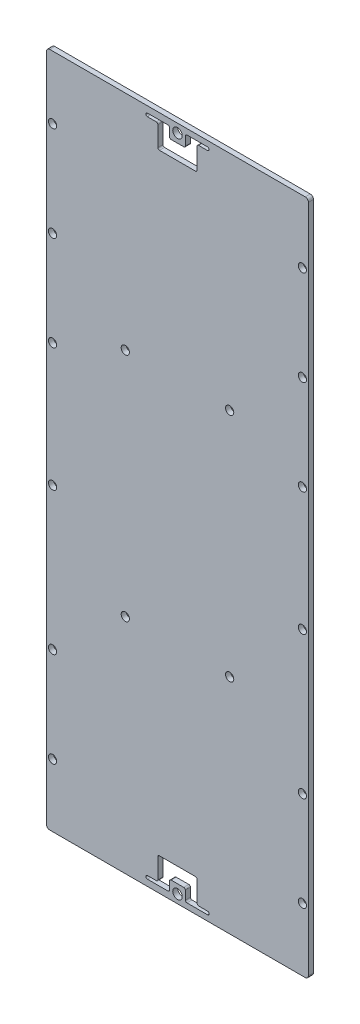
SolidWorks part; units mm, degrees
ref_plane "Front Plane" through (0, 0, 0) normal (0, 0, 1) x (1, 0, 0)
ref_plane "Top Plane" through (0, 0, 0) normal (0, 1, 0) x (1, 0, 0)
ref_plane "Right Plane" through (0, 0, 0) normal (1, 0, 0) x (0, 0, -1)
sketch "Sketch1" plane through (0, 0, 0) normal (0, 0, 1) x (1, 0, 0)
  line L0 (-37, -97) -> (37, -97) construction
  line L5 (-37, -95.4) -> (37, -95.4) construction
  line L6 (-37, -87) -> (37, -87) construction
  line L7 (-37, -85.4) -> (37, -85.4) construction
  line L8 (-37, -77) -> (37, -77) construction
  line L9 (-37, -75.4) -> (37, -75.4) construction
  line L10 (-37, -67) -> (37, -67) construction
  line L11 (-37, -65.4) -> (37, -65.4) construction
  line L12 (-37, -57) -> (37, -57) construction
  line L13 (-37, -55.4) -> (37, -55.4) construction
  line L14 (-37, -47) -> (37, -47) construction
  line L15 (-37, -45.4) -> (37, -45.4) construction
  line L16 (-37, -37) -> (37, -37) construction
  line L17 (-37, -35.4) -> (37, -35.4) construction
  line L18 (-37, -27) -> (37, -27) construction
  line L19 (-37, -25.4) -> (37, -25.4) construction
  line L20 (-37, -17) -> (37, -17) construction
  line L21 (-37, -15.4) -> (37, -15.4) construction
  line L22 (-37, 15.4) -> (37, 15.4) construction
  line L23 (-37, 17) -> (37, 17) construction
  line L24 (-37, 25.4) -> (37, 25.4) construction
  line L25 (-37, 27) -> (37, 27) construction
  line L26 (-37, 35.4) -> (37, 35.4) construction
  line L27 (-37, 37) -> (37, 37) construction
  line L28 (41.5, 107) -> (-41.5, 107)
  line L29 (-41.5, 107) -> (-41.5, 99)
  line L30 (-41.5, 99) -> (-41.5, 93.95)
  line L31 (-41.5, 93.95) -> (-41.5, 88.45)
  line L32 (-41.5, 88.45) -> (-41.5, 33.95)
  line L33 (-41.5, 33.95) -> (-41.5, 28.45)
  line L34 (-41.5, 28.45) -> (-41.5, -28.45)
  line L35 (-41.5, -28.45) -> (-41.5, -33.95)
  line L36 (-41.5, -33.95) -> (-41.5, -88.45)
  line L37 (-41.5, -88.45) -> (-41.5, -93.95)
  line L38 (-41.5, -93.95) -> (-41.5, -99)
  line L39 (-41.5, -99) -> (-41.5, -107)
  line L40 (-41.5, -107) -> (41.5, -107)
  line L41 (41.5, -107) -> (41.5, -99)
  line L42 (41.5, -99) -> (41.5, -93.95)
  line L43 (41.5, -93.95) -> (41.5, -88.45)
  line L44 (41.5, -88.45) -> (41.5, -33.95)
  line L45 (41.5, -33.95) -> (41.5, -28.45)
  line L46 (41.5, -28.45) -> (41.5, 28.45)
  line L47 (41.5, 28.45) -> (41.5, 33.95)
  line L48 (41.5, 33.95) -> (41.5, 88.45)
  line L49 (41.5, 88.45) -> (41.5, 93.95)
  line L50 (41.5, 93.95) -> (41.5, 99)
  line L51 (41.5, 99) -> (41.5, 107)
  line L52 (41.5, 107) -> (-41.5, 107)
  line L53 (-41.5, 107) -> (-41.5, 99)
  line L54 (-41.5, 99) -> (-41.5, 93.95)
  line L55 (-41.5, 93.95) -> (-41.5, 88.45)
  line L56 (-41.5, 88.45) -> (-41.5, 33.95)
  line L57 (-41.5, 33.95) -> (-41.5, 28.45)
  line L58 (-41.5, 28.45) -> (-41.5, -28.45)
  line L59 (-41.5, -28.45) -> (-41.5, -33.95)
  line L60 (-41.5, -33.95) -> (-41.5, -88.45)
  line L61 (-41.5, -88.45) -> (-41.5, -93.95)
  line L62 (-41.5, -93.95) -> (-41.5, -99)
  line L63 (-41.5, -99) -> (-41.5, -107)
  line L64 (-41.5, -107) -> (41.5, -107)
  line L65 (41.5, -107) -> (41.5, -99)
  line L66 (41.5, -99) -> (41.5, -93.95)
  line L67 (41.5, -93.95) -> (41.5, -88.45)
  line L68 (41.5, -88.45) -> (41.5, -33.95)
  line L69 (41.5, -33.95) -> (41.5, -28.45)
  line L70 (41.5, -28.45) -> (41.5, 28.45)
  line L71 (41.5, 28.45) -> (41.5, 33.95)
  line L72 (41.5, 33.95) -> (41.5, 88.45)
  line L73 (41.5, 88.45) -> (41.5, 93.95)
  line L74 (41.5, 93.95) -> (41.5, 99)
  line L75 (41.5, 99) -> (41.5, 107)
  line L76 (-37, 45.4) -> (37, 45.4) construction
  line L77 (-37, 47) -> (37, 47) construction
  line L78 (-37, 55.4) -> (37, 55.4) construction
  line L79 (-37, 57) -> (37, 57) construction
  line L80 (-37, 65.4) -> (37, 65.4) construction
  line L81 (-37, 67) -> (37, 67) construction
  line L82 (-37, 75.4) -> (37, 75.4) construction
  line L83 (-37, 77) -> (37, 77) construction
  line L84 (-37, 85.4) -> (37, 85.4) construction
  line L85 (-37, 87) -> (37, 87) construction
  line L86 (-37, 95.4) -> (37, 95.4) construction
  line L87 (-37, 97) -> (37, 97) construction
  line L88 (-37, -97) -> (37, -97) construction
  line L89 (-37, -95.4) -> (37, -95.4) construction
  line L90 (-37, -87) -> (37, -87) construction
  line L91 (-37, -85.4) -> (37, -85.4) construction
  line L92 (-37, -77) -> (37, -77) construction
  line L93 (-37, -75.4) -> (37, -75.4) construction
  line L94 (-37, -67) -> (37, -67) construction
  line L95 (-37, -65.4) -> (37, -65.4) construction
  line L96 (-37, -57) -> (37, -57) construction
  line L97 (-37, -55.4) -> (37, -55.4) construction
  line L98 (-37, -47) -> (37, -47) construction
  line L99 (-37, -45.4) -> (37, -45.4) construction
  line L100 (-37, -37) -> (37, -37) construction
  line L101 (-37, -35.4) -> (37, -35.4) construction
  line L102 (-37, -27) -> (37, -27) construction
  line L103 (-37, -25.4) -> (37, -25.4) construction
  line L104 (-37, -17) -> (37, -17) construction
  line L105 (-37, -15.4) -> (37, -15.4) construction
  line L106 (-37, 15.4) -> (37, 15.4) construction
  line L107 (-37, 17) -> (37, 17) construction
  line L108 (-37, 25.4) -> (37, 25.4) construction
  line L109 (-37, 27) -> (37, 27) construction
  line L110 (-37, 35.4) -> (37, 35.4) construction
  line L111 (-37, 37) -> (37, 37) construction
  line L112 (-37, 45.4) -> (37, 45.4) construction
  line L113 (-37, 47) -> (37, 47) construction
  line L114 (-37, 55.4) -> (37, 55.4) construction
  line L115 (-37, 57) -> (37, 57) construction
  line L116 (-37, 65.4) -> (37, 65.4) construction
  line L117 (-37, 67) -> (37, 67) construction
  line L118 (-37, 75.4) -> (37, 75.4) construction
  line L119 (-37, 77) -> (37, 77) construction
  line L120 (-37, 85.4) -> (37, 85.4) construction
  line L121 (-37, 87) -> (37, 87) construction
  line L122 (-37, 95.4) -> (37, 95.4) construction
  line L123 (-37, 97) -> (37, 97) construction
  line L124 (41.4, 106.9) -> (-41.4, 106.9)
  line L125 (-41.4, 106.9) -> (-41.4, 99)
  line L126 (-41.4, 99) -> (-41.4, 93.95)
  line L127 (-41.4, 93.95) -> (-41.4, 88.45)
  line L128 (-41.4, 88.45) -> (-41.4, 33.95)
  line L129 (-41.4, 33.95) -> (-41.4, 28.45)
  line L130 (-41.4, 28.45) -> (-41.4, -28.45)
  line L131 (-41.4, -28.45) -> (-41.4, -33.95)
  line L132 (-41.4, -33.95) -> (-41.4, -88.45)
  line L133 (-41.4, -88.45) -> (-41.4, -93.95)
  line L134 (-41.4, -93.95) -> (-41.4, -99)
  line L135 (-41.4, -99) -> (-41.4, -106.9)
  line L136 (-41.4, -106.9) -> (41.4, -106.9)
  line L137 (41.4, -106.9) -> (41.4, -99)
  line L138 (41.4, -99) -> (41.4, -93.95)
  line L139 (41.4, -93.95) -> (41.4, -88.45)
  line L140 (41.4, -88.45) -> (41.4, -33.95)
  line L141 (41.4, -33.95) -> (41.4, -28.45)
  line L142 (41.4, -28.45) -> (41.4, 28.45)
  line L143 (41.4, 28.45) -> (41.4, 33.95)
  line L144 (41.4, 33.95) -> (41.4, 88.45)
  line L145 (41.4, 88.45) -> (41.4, 93.95)
  line L146 (41.4, 93.95) -> (41.4, 99)
  line L147 (41.4, 99) -> (41.4, 106.9)
  circle A0 centre (-39.5, 87) radius 0.8 construction
  circle A2 centre (-39.5, 57) radius 0.8 construction
  circle A5 centre (-39.5, 27) radius 0.8 construction
  circle A6 centre (-16.5, 36.5) radius 0.8 construction
  circle A7 centre (-39.5, -12) radius 0.8 construction
  circle A9 centre (-16.5, -36.5) radius 0.8 construction
  circle A11 centre (-39.5, -57) radius 0.8 construction
  circle A13 centre (-39.5, -87) radius 0.8 construction
  circle A16 centre (0, -104.2) radius 0.8 construction
  circle A19 centre (39.5, -87) radius 0.8 construction
  circle A21 centre (39.5, -57) radius 0.8 construction
  circle A22 centre (16.5, -36.5) radius 0.8 construction
  circle A25 centre (39.5, -12) radius 0.8 construction
  circle A27 centre (39.5, 27) radius 0.8 construction
  circle A28 centre (16.5, 36.5) radius 0.8 construction
  circle A30 centre (39.5, 57) radius 0.8 construction
  circle A32 centre (39.5, 87) radius 0.8 construction
  circle A35 centre (0, 104.2) radius 0.8 construction
  circle A38 centre (-39.5, 87) radius 0.8
  circle A40 centre (-39.5, 57) radius 0.8
  circle A43 centre (-39.5, 27) radius 0.8
  circle A44 centre (-16.5, 36.5) radius 0.8
  circle A45 centre (-39.5, -12) radius 0.8
  circle A47 centre (-16.5, -36.5) radius 0.8
  circle A49 centre (-39.5, -57) radius 0.8
  circle A51 centre (-39.5, -87) radius 0.8
  circle A54 centre (0, -104.2) radius 0.8
  circle A57 centre (39.5, -87) radius 0.8
  circle A59 centre (39.5, -57) radius 0.8
  circle A60 centre (16.5, -36.5) radius 0.8
  circle A63 centre (39.5, -12) radius 0.8
  circle A65 centre (39.5, 27) radius 0.8
  circle A66 centre (16.5, 36.5) radius 0.8
  circle A68 centre (39.5, 57) radius 0.8
  circle A70 centre (39.5, 87) radius 0.8
  circle A73 centre (0, 104.2) radius 0.8
  dimension "D1" = 0
  dimension "D2" = 0.1
extrude "pcb extrude" add sketch "Sketch1" along normal blind 1.6
sketch "connector locations" plane through (0, 0, 1.6) normal (0, 0, 1) x (1, 0, 0)
  line L0 (-37, 97) -> (37, 97) construction
  line L1 (-33.4182, 100.556) -> (-8.7802, 100.556)
  line L2 (-33.4182, 100.556) -> (-33.4182, 99.159)
  line L3 (-33.4182, 99.159) -> (-8.7802, 99.159)
  line L4 (-8.7802, 100.556) -> (-8.7802, 99.159)
  line L5 (-33.4182, 100.556) -> (-8.7802, 99.159) construction
  line L6 (-33.4182, 99.159) -> (-8.7802, 100.556) construction
  line L7 (-37, 87) -> (37, 87) construction
  line L8 (-33.4182, 90.556) -> (-21.5818, 90.556)
  line L9 (-33.4182, 90.556) -> (-33.4182, 89.159)
  line L10 (-33.4182, 89.159) -> (-21.5818, 89.159)
  line L11 (-21.5818, 90.556) -> (-21.5818, 89.159)
  line L12 (-33.4182, 90.556) -> (-21.5818, 89.159) construction
  line L13 (-33.4182, 89.159) -> (-21.5818, 90.556) construction
  line L14 (0, -55) -> (0, 55) construction
  line L15 (-12.319, 90.556) -> (12.319, 90.556)
  line L16 (-12.319, 90.556) -> (-12.319, 89.159)
  line L17 (-12.319, 89.159) -> (12.319, 89.159)
  line L18 (12.319, 90.556) -> (12.319, 89.159)
  line L19 (-12.319, 90.556) -> (12.319, 89.159) construction
  line L20 (-12.319, 89.159) -> (12.319, 90.556) construction
  line L21 (-37, -85.4) -> (37, -85.4) construction
  line L22 (-33.4182, -91.844) -> (-8.7802, -91.844)
  line L23 (-33.4182, -91.844) -> (-33.4182, -93.241)
  line L24 (-33.4182, -93.241) -> (-8.7802, -93.241)
  line L25 (-8.7802, -91.844) -> (-8.7802, -93.241)
  line L26 (-33.4182, -91.844) -> (-8.7802, -93.241) construction
  line L27 (-33.4182, -93.241) -> (-8.7802, -91.844) construction
  line L28 (-33.4182, -81.844) -> (-21.5818, -81.844)
  line L29 (-33.4182, -81.844) -> (-33.4182, -83.241)
  line L30 (-33.4182, -83.241) -> (-21.5818, -83.241)
  line L31 (-21.5818, -81.844) -> (-21.5818, -83.241)
  line L32 (-33.4182, -81.844) -> (-21.5818, -83.241) construction
  line L33 (-33.4182, -83.241) -> (-21.5818, -81.844) construction
  line L34 (-12.319, -81.844) -> (12.319, -81.844)
  line L35 (-12.319, -81.844) -> (-12.319, -83.241)
  line L36 (-12.319, -83.241) -> (12.319, -83.241)
  line L37 (12.319, -81.844) -> (12.319, -83.241)
  line L38 (-12.319, -81.844) -> (12.319, -83.241) construction
  line L39 (-12.319, -83.241) -> (12.319, -81.844) construction
  line L40 (-37, -95.4) -> (37, -95.4) construction
  line L41 (-33.4182, 80.556) -> (-33.4182, 79.159)
  line L42 (-33.4182, 80.556) -> (-21.5818, 80.556)
  line L43 (-21.5818, 80.556) -> (-21.5818, 79.159)
  line L44 (-33.4182, 79.159) -> (-21.5818, 79.159)
  line L45 (-33.4182, 80.556) -> (-21.5818, 79.159) construction
  line L46 (-33.4182, 79.159) -> (-21.5818, 80.556) construction
  line L47 (-12.319, 80.556) -> (-12.319, 79.159)
  line L48 (-12.319, 80.556) -> (12.319, 80.556)
  line L49 (12.319, 80.556) -> (12.319, 79.159)
  line L50 (-12.319, 79.159) -> (12.319, 79.159)
  line L51 (-12.319, 80.556) -> (12.319, 79.159) construction
  line L52 (-12.319, 79.159) -> (12.319, 80.556) construction
  line L53 (-33.4182, 70.556) -> (-33.4182, 69.159)
  line L54 (-33.4182, 70.556) -> (-21.5818, 70.556)
  line L55 (-21.5818, 70.556) -> (-21.5818, 69.159)
  line L56 (-33.4182, 69.159) -> (-21.5818, 69.159)
  line L57 (-33.4182, 70.556) -> (-21.5818, 69.159) construction
  line L58 (-33.4182, 69.159) -> (-21.5818, 70.556) construction
  line L59 (-12.319, 70.556) -> (-12.319, 69.159)
  line L60 (-12.319, 70.556) -> (12.319, 70.556)
  line L61 (12.319, 70.556) -> (12.319, 69.159)
  line L62 (-12.319, 69.159) -> (12.319, 69.159)
  line L63 (-12.319, 70.556) -> (12.319, 69.159) construction
  line L64 (-12.319, 69.159) -> (12.319, 70.556) construction
  line L65 (-33.4182, 60.556) -> (-33.4182, 59.159)
  line L66 (-33.4182, 60.556) -> (-21.5818, 60.556)
  line L67 (-21.5818, 60.556) -> (-21.5818, 59.159)
  line L68 (-33.4182, 59.159) -> (-21.5818, 59.159)
  line L69 (-33.4182, 60.556) -> (-21.5818, 59.159) construction
  line L70 (-33.4182, 59.159) -> (-21.5818, 60.556) construction
  line L71 (-12.319, 60.556) -> (-12.319, 59.159)
  line L72 (-12.319, 60.556) -> (12.319, 60.556)
  line L73 (12.319, 60.556) -> (12.319, 59.159)
  line L74 (-12.319, 59.159) -> (12.319, 59.159)
  line L75 (-12.319, 60.556) -> (12.319, 59.159) construction
  line L76 (-12.319, 59.159) -> (12.319, 60.556) construction
  line L77 (-33.4182, 50.556) -> (-33.4182, 49.159)
  line L78 (-33.4182, 50.556) -> (-21.5818, 50.556)
  line L79 (-21.5818, 50.556) -> (-21.5818, 49.159)
  line L80 (-33.4182, 49.159) -> (-21.5818, 49.159)
  line L81 (-33.4182, 50.556) -> (-21.5818, 49.159) construction
  line L82 (-33.4182, 49.159) -> (-21.5818, 50.556) construction
  line L83 (-12.319, 50.556) -> (-12.319, 49.159)
  line L84 (-12.319, 50.556) -> (12.319, 50.556)
  line L85 (12.319, 50.556) -> (12.319, 49.159)
  line L86 (-12.319, 49.159) -> (12.319, 49.159)
  line L87 (-12.319, 50.556) -> (12.319, 49.159) construction
  line L88 (-12.319, 49.159) -> (12.319, 50.556) construction
  line L89 (-33.4182, 40.556) -> (-33.4182, 39.159)
  line L90 (-33.4182, 40.556) -> (-21.5818, 40.556)
  line L91 (-21.5818, 40.556) -> (-21.5818, 39.159)
  line L92 (-33.4182, 39.159) -> (-21.5818, 39.159)
  line L93 (-33.4182, 40.556) -> (-21.5818, 39.159) construction
  line L94 (-33.4182, 39.159) -> (-21.5818, 40.556) construction
  line L95 (-12.319, 40.556) -> (-12.319, 39.159)
  line L96 (-12.319, 40.556) -> (12.319, 40.556)
  line L97 (12.319, 40.556) -> (12.319, 39.159)
  line L98 (-12.319, 39.159) -> (12.319, 39.159)
  line L99 (-12.319, 40.556) -> (12.319, 39.159) construction
  line L100 (-12.319, 39.159) -> (12.319, 40.556) construction
  line L101 (-33.4182, 30.556) -> (-33.4182, 29.159)
  line L102 (-33.4182, 30.556) -> (-21.5818, 30.556)
  line L103 (-21.5818, 30.556) -> (-21.5818, 29.159)
  line L104 (-33.4182, 29.159) -> (-21.5818, 29.159)
  line L105 (-33.4182, 30.556) -> (-21.5818, 29.159) construction
  line L106 (-33.4182, 29.159) -> (-21.5818, 30.556) construction
  line L107 (-12.319, 30.556) -> (-12.319, 29.159)
  line L108 (-12.319, 30.556) -> (12.319, 30.556)
  line L109 (12.319, 30.556) -> (12.319, 29.159)
  line L110 (-12.319, 29.159) -> (12.319, 29.159)
  line L111 (-12.319, 30.556) -> (12.319, 29.159) construction
  line L112 (-12.319, 29.159) -> (12.319, 30.556) construction
  line L113 (-33.4182, 20.556) -> (-33.4182, 19.159)
  line L114 (-33.4182, 20.556) -> (-21.5818, 20.556)
  line L115 (-21.5818, 20.556) -> (-21.5818, 19.159)
  line L116 (-33.4182, 19.159) -> (-21.5818, 19.159)
  line L117 (-33.4182, 20.556) -> (-21.5818, 19.159) construction
  line L118 (-33.4182, 19.159) -> (-21.5818, 20.556) construction
  line L119 (-12.319, 20.556) -> (-12.319, 19.159)
  line L120 (-12.319, 20.556) -> (12.319, 20.556)
  line L121 (12.319, 20.556) -> (12.319, 19.159)
  line L122 (-12.319, 19.159) -> (12.319, 19.159)
  line L123 (-12.319, 20.556) -> (12.319, 19.159) construction
  line L124 (-12.319, 19.159) -> (12.319, 20.556) construction
  line L125 (-33.4182, 10.556) -> (-33.4182, 9.159)
  line L126 (-33.4182, 10.556) -> (-21.5818, 10.556)
  line L127 (-21.5818, 10.556) -> (-21.5818, 9.159)
  line L128 (-33.4182, 9.159) -> (-21.5818, 9.159)
  line L129 (-33.4182, 10.556) -> (-21.5818, 9.159) construction
  line L130 (-33.4182, 9.159) -> (-21.5818, 10.556) construction
  line L131 (-12.319, 10.556) -> (-12.319, 9.159)
  line L132 (-12.319, 10.556) -> (12.319, 10.556)
  line L133 (12.319, 10.556) -> (12.319, 9.159)
  line L134 (-12.319, 9.159) -> (12.319, 9.159)
  line L135 (-12.319, 10.556) -> (12.319, 9.159) construction
  line L136 (-12.319, 9.159) -> (12.319, 10.556) construction
  line L137 (0, 89.8575) -> (0, 79.8575) construction
  line L138 (-33.4182, -71.844) -> (-33.4182, -73.241)
  line L139 (-33.4182, -71.844) -> (-21.5818, -71.844)
  line L140 (-21.5818, -71.844) -> (-21.5818, -73.241)
  line L141 (-33.4182, -73.241) -> (-21.5818, -73.241)
  line L142 (-33.4182, -73.241) -> (-21.5818, -71.844) construction
  line L143 (-33.4182, -71.844) -> (-21.5818, -73.241) construction
  line L144 (-12.319, -71.844) -> (-12.319, -73.241)
  line L145 (-12.319, -71.844) -> (12.319, -71.844)
  line L146 (12.319, -71.844) -> (12.319, -73.241)
  line L147 (-12.319, -73.241) -> (12.319, -73.241)
  line L148 (-12.319, -73.241) -> (12.319, -71.844) construction
  line L149 (-12.319, -71.844) -> (12.319, -73.241) construction
  line L150 (-33.4182, -61.844) -> (-33.4182, -63.241)
  line L151 (-33.4182, -61.844) -> (-21.5818, -61.844)
  line L152 (-21.5818, -61.844) -> (-21.5818, -63.241)
  line L153 (-33.4182, -63.241) -> (-21.5818, -63.241)
  line L154 (-33.4182, -63.241) -> (-21.5818, -61.844) construction
  line L155 (-33.4182, -61.844) -> (-21.5818, -63.241) construction
  line L156 (-12.319, -61.844) -> (-12.319, -63.241)
  line L157 (-12.319, -61.844) -> (12.319, -61.844)
  line L158 (12.319, -61.844) -> (12.319, -63.241)
  line L159 (-12.319, -63.241) -> (12.319, -63.241)
  line L160 (-12.319, -63.241) -> (12.319, -61.844) construction
  line L161 (-12.319, -61.844) -> (12.319, -63.241) construction
  line L162 (-33.4182, -51.844) -> (-33.4182, -53.241)
  line L163 (-33.4182, -51.844) -> (-21.5818, -51.844)
  line L164 (-21.5818, -51.844) -> (-21.5818, -53.241)
  line L165 (-33.4182, -53.241) -> (-21.5818, -53.241)
  line L166 (-33.4182, -53.241) -> (-21.5818, -51.844) construction
  line L167 (-33.4182, -51.844) -> (-21.5818, -53.241) construction
  line L168 (-12.319, -51.844) -> (-12.319, -53.241)
  line L169 (-12.319, -51.844) -> (12.319, -51.844)
  line L170 (12.319, -51.844) -> (12.319, -53.241)
  line L171 (-12.319, -53.241) -> (12.319, -53.241)
  line L172 (-12.319, -53.241) -> (12.319, -51.844) construction
  line L173 (-12.319, -51.844) -> (12.319, -53.241) construction
  line L174 (-33.4182, -41.844) -> (-33.4182, -43.241)
  line L175 (-33.4182, -41.844) -> (-21.5818, -41.844)
  line L176 (-21.5818, -41.844) -> (-21.5818, -43.241)
  line L177 (-33.4182, -43.241) -> (-21.5818, -43.241)
  line L178 (-33.4182, -43.241) -> (-21.5818, -41.844) construction
  line L179 (-33.4182, -41.844) -> (-21.5818, -43.241) construction
  line L180 (-12.319, -41.844) -> (-12.319, -43.241)
  line L181 (-12.319, -41.844) -> (12.319, -41.844)
  line L182 (12.319, -41.844) -> (12.319, -43.241)
  line L183 (-12.319, -43.241) -> (12.319, -43.241)
  line L184 (-12.319, -43.241) -> (12.319, -41.844) construction
  line L185 (-12.319, -41.844) -> (12.319, -43.241) construction
  line L186 (-33.4182, -31.844) -> (-33.4182, -33.241)
  line L187 (-33.4182, -31.844) -> (-21.5818, -31.844)
  line L188 (-21.5818, -31.844) -> (-21.5818, -33.241)
  line L189 (-33.4182, -33.241) -> (-21.5818, -33.241)
  line L190 (-33.4182, -33.241) -> (-21.5818, -31.844) construction
  line L191 (-33.4182, -31.844) -> (-21.5818, -33.241) construction
  line L192 (-12.319, -31.844) -> (-12.319, -33.241)
  line L193 (-12.319, -31.844) -> (12.319, -31.844)
  line L194 (12.319, -31.844) -> (12.319, -33.241)
  line L195 (-12.319, -33.241) -> (12.319, -33.241)
  line L196 (-12.319, -33.241) -> (12.319, -31.844) construction
  line L197 (-12.319, -31.844) -> (12.319, -33.241) construction
  line L198 (-33.4182, -21.844) -> (-33.4182, -23.241)
  line L199 (-33.4182, -21.844) -> (-21.5818, -21.844)
  line L200 (-21.5818, -21.844) -> (-21.5818, -23.241)
  line L201 (-33.4182, -23.241) -> (-21.5818, -23.241)
  line L202 (-33.4182, -23.241) -> (-21.5818, -21.844) construction
  line L203 (-33.4182, -21.844) -> (-21.5818, -23.241) construction
  line L204 (-12.319, -21.844) -> (-12.319, -23.241)
  line L205 (-12.319, -21.844) -> (12.319, -21.844)
  line L206 (12.319, -21.844) -> (12.319, -23.241)
  line L207 (-12.319, -23.241) -> (12.319, -23.241)
  line L208 (-12.319, -23.241) -> (12.319, -21.844) construction
  line L209 (-12.319, -21.844) -> (12.319, -23.241) construction
  line L210 (-33.4182, -11.844) -> (-33.4182, -13.241)
  line L211 (-33.4182, -11.844) -> (-21.5818, -11.844)
  line L212 (-21.5818, -11.844) -> (-21.5818, -13.241)
  line L213 (-33.4182, -13.241) -> (-21.5818, -13.241)
  line L214 (-33.4182, -13.241) -> (-21.5818, -11.844) construction
  line L215 (-33.4182, -11.844) -> (-21.5818, -13.241) construction
  line L216 (-12.319, -11.844) -> (-12.319, -13.241)
  line L217 (-12.319, -11.844) -> (12.319, -11.844)
  line L218 (12.319, -11.844) -> (12.319, -13.241)
  line L219 (-12.319, -13.241) -> (12.319, -13.241)
  line L220 (-12.319, -13.241) -> (12.319, -11.844) construction
  line L221 (-12.319, -11.844) -> (12.319, -13.241) construction
  line L222 (-33.4182, -1.844) -> (-33.4182, -3.241)
  line L223 (-33.4182, -1.844) -> (-21.5818, -1.844)
  line L224 (-21.5818, -1.844) -> (-21.5818, -3.241)
  line L225 (-33.4182, -3.241) -> (-21.5818, -3.241)
  line L226 (-33.4182, -3.241) -> (-21.5818, -1.844) construction
  line L227 (-33.4182, -1.844) -> (-21.5818, -3.241) construction
  line L228 (-12.319, -1.844) -> (-12.319, -3.241)
  line L229 (-12.319, -1.844) -> (12.319, -1.844)
  line L230 (12.319, -1.844) -> (12.319, -3.241)
  line L231 (-12.319, -3.241) -> (12.319, -3.241)
  line L232 (-12.319, -3.241) -> (12.319, -1.844) construction
  line L233 (-12.319, -1.844) -> (12.319, -3.241) construction
  line L234 (0, -82.5425) -> (0, -72.5425) construction
  line L235 (27.42, 96.09) -> (29.58, 98.27) construction
  line L236 (27.42, 98.27) -> (29.58, 96.09) construction
  line L237 (33.42, 98.27) -> (35.58, 96.09) construction
  line L238 (33.42, 96.09) -> (35.58, 98.27) construction
  line L239 (21.42, 96.09) -> (23.58, 98.27) construction
  line L240 (21.42, 98.27) -> (23.58, 96.09) construction
  line L241 (27.42, 86.09) -> (29.58, 88.27) construction
  line L242 (27.42, 88.27) -> (29.58, 86.09) construction
  line L243 (21.42, 86.09) -> (23.58, 88.27) construction
  line L244 (21.42, 88.27) -> (23.58, 86.09) construction
  line L245 (27.42, 76.09) -> (29.58, 78.27) construction
  line L246 (27.42, 78.27) -> (29.58, 76.09) construction
  line L247 (21.42, 76.09) -> (23.58, 78.27) construction
  line L248 (21.42, 78.27) -> (23.58, 76.09) construction
  line L249 (27.42, 66.09) -> (29.58, 68.27) construction
  line L250 (27.42, 68.27) -> (29.58, 66.09) construction
  line L251 (21.42, 66.09) -> (23.58, 68.27) construction
  line L252 (21.42, 68.27) -> (23.58, 66.09) construction
  line L253 (27.42, 56.09) -> (29.58, 58.27) construction
  line L254 (27.42, 58.27) -> (29.58, 56.09) construction
  line L255 (21.42, 56.09) -> (23.58, 58.27) construction
  line L256 (21.42, 58.27) -> (23.58, 56.09) construction
  line L257 (27.42, 46.09) -> (29.58, 48.27) construction
  line L258 (27.42, 48.27) -> (29.58, 46.09) construction
  line L259 (21.42, 46.09) -> (23.58, 48.27) construction
  line L260 (21.42, 48.27) -> (23.58, 46.09) construction
  line L261 (27.42, 36.09) -> (29.58, 38.27) construction
  line L262 (27.42, 38.27) -> (29.58, 36.09) construction
  line L263 (21.42, 36.09) -> (23.58, 38.27) construction
  line L264 (21.42, 38.27) -> (23.58, 36.09) construction
  line L265 (27.42, 26.09) -> (29.58, 28.27) construction
  line L266 (27.42, 28.27) -> (29.58, 26.09) construction
  line L267 (21.42, 26.09) -> (23.58, 28.27) construction
  line L268 (21.42, 28.27) -> (23.58, 26.09) construction
  line L269 (27.42, 16.09) -> (29.58, 18.27) construction
  line L270 (27.42, 18.27) -> (29.58, 16.09) construction
  line L271 (21.42, 16.09) -> (23.58, 18.27) construction
  line L272 (21.42, 18.27) -> (23.58, 16.09) construction
  line L273 (27.42, 6.09) -> (29.58, 8.27) construction
  line L274 (27.42, 8.27) -> (29.58, 6.09) construction
  line L275 (21.42, 6.09) -> (23.58, 8.27) construction
  line L276 (21.42, 8.27) -> (23.58, 6.09) construction
  line L277 (33.42, 86.09) -> (35.58, 88.27) construction
  line L278 (33.42, 88.27) -> (35.58, 86.09) construction
  line L279 (33.42, 76.09) -> (35.58, 78.27) construction
  line L280 (33.42, 78.27) -> (35.58, 76.09) construction
  line L281 (33.42, 66.09) -> (35.58, 68.27) construction
  line L282 (33.42, 68.27) -> (35.58, 66.09) construction
  line L283 (33.42, 56.09) -> (35.58, 58.27) construction
  line L284 (33.42, 58.27) -> (35.58, 56.09) construction
  line L285 (33.42, 46.09) -> (35.58, 48.27) construction
  line L286 (33.42, 48.27) -> (35.58, 46.09) construction
  line L287 (33.42, 36.09) -> (35.58, 38.27) construction
  line L288 (33.42, 38.27) -> (35.58, 36.09) construction
  line L289 (33.42, 26.09) -> (35.58, 28.27) construction
  line L290 (33.42, 28.27) -> (35.58, 26.09) construction
  line L291 (33.42, 16.09) -> (35.58, 18.27) construction
  line L292 (33.42, 18.27) -> (35.58, 16.09) construction
  line L293 (33.42, 6.09) -> (35.58, 8.27) construction
  line L294 (33.42, 8.27) -> (35.58, 6.09) construction
  line L295 (33.42, 98.27) -> (27.42, 98.27) construction
  line L296 (33.42, 98.27) -> (33.42, 88.27) construction
  line L297 (33.42, -94.13) -> (35.58, -96.31) construction
  line L298 (35.58, -94.13) -> (33.42, -96.31) construction
  line L299 (29.58, -94.13) -> (27.42, -96.31) construction
  line L300 (27.42, -94.13) -> (29.58, -96.31) construction
  line L301 (23.58, -94.13) -> (21.42, -96.31) construction
  line L302 (21.42, -94.13) -> (23.58, -96.31) construction
  line L303 (29.58, -84.13) -> (27.42, -86.31) construction
  line L304 (27.42, -84.13) -> (29.58, -86.31) construction
  line L305 (23.58, -84.13) -> (21.42, -86.31) construction
  line L306 (21.42, -84.13) -> (23.58, -86.31) construction
  line L307 (29.58, -74.13) -> (27.42, -76.31) construction
  line L308 (27.42, -74.13) -> (29.58, -76.31) construction
  line L309 (23.58, -74.13) -> (21.42, -76.31) construction
  line L310 (21.42, -74.13) -> (23.58, -76.31) construction
  line L311 (29.58, -64.13) -> (27.42, -66.31) construction
  line L312 (27.42, -64.13) -> (29.58, -66.31) construction
  line L313 (23.58, -64.13) -> (21.42, -66.31) construction
  line L314 (21.42, -64.13) -> (23.58, -66.31) construction
  line L315 (29.58, -54.13) -> (27.42, -56.31) construction
  line L316 (27.42, -54.13) -> (29.58, -56.31) construction
  line L317 (23.58, -54.13) -> (21.42, -56.31) construction
  line L318 (21.42, -54.13) -> (23.58, -56.31) construction
  line L319 (29.58, -44.13) -> (27.42, -46.31) construction
  line L320 (27.42, -44.13) -> (29.58, -46.31) construction
  line L321 (23.58, -44.13) -> (21.42, -46.31) construction
  line L322 (21.42, -44.13) -> (23.58, -46.31) construction
  line L323 (29.58, -34.13) -> (27.42, -36.31) construction
  line L324 (27.42, -34.13) -> (29.58, -36.31) construction
  line L325 (23.58, -34.13) -> (21.42, -36.31) construction
  line L326 (21.42, -34.13) -> (23.58, -36.31) construction
  line L327 (29.58, -24.13) -> (27.42, -26.31) construction
  line L328 (27.42, -24.13) -> (29.58, -26.31) construction
  line L329 (23.58, -24.13) -> (21.42, -26.31) construction
  line L330 (21.42, -24.13) -> (23.58, -26.31) construction
  line L331 (29.58, -14.13) -> (27.42, -16.31) construction
  line L332 (27.42, -14.13) -> (29.58, -16.31) construction
  line L333 (23.58, -14.13) -> (21.42, -16.31) construction
  line L334 (21.42, -14.13) -> (23.58, -16.31) construction
  line L335 (29.58, -4.13) -> (27.42, -6.31) construction
  line L336 (27.42, -4.13) -> (29.58, -6.31) construction
  line L337 (23.58, -4.13) -> (21.42, -6.31) construction
  line L338 (21.42, -4.13) -> (23.58, -6.31) construction
  line L339 (35.58, -84.13) -> (33.42, -86.31) construction
  line L340 (33.42, -84.13) -> (35.58, -86.31) construction
  line L341 (35.58, -74.13) -> (33.42, -76.31) construction
  line L342 (33.42, -74.13) -> (35.58, -76.31) construction
  line L343 (35.58, -64.13) -> (33.42, -66.31) construction
  line L344 (33.42, -64.13) -> (35.58, -66.31) construction
  line L345 (35.58, -54.13) -> (33.42, -56.31) construction
  line L346 (33.42, -54.13) -> (35.58, -56.31) construction
  line L347 (35.58, -44.13) -> (33.42, -46.31) construction
  line L348 (33.42, -44.13) -> (35.58, -46.31) construction
  line L349 (35.58, -34.13) -> (33.42, -36.31) construction
  line L350 (33.42, -34.13) -> (35.58, -36.31) construction
  line L351 (35.58, -24.13) -> (33.42, -26.31) construction
  line L352 (33.42, -24.13) -> (35.58, -26.31) construction
  line L353 (35.58, -14.13) -> (33.42, -16.31) construction
  line L354 (33.42, -14.13) -> (35.58, -16.31) construction
  line L355 (35.58, -4.13) -> (33.42, -6.31) construction
  line L356 (33.42, -4.13) -> (35.58, -6.31) construction
  line L357 (33.42, -94.13) -> (27.42, -94.13) construction
  line L358 (33.42, -94.13) -> (33.42, -84.13) construction
  circle A0 centre (33.42, 98.27) radius 0.32
  circle A1 centre (35.58, 98.27) radius 0.32
  circle A2 centre (35.58, 96.09) radius 0.32
  circle A3 centre (33.42, 96.09) radius 0.32
  circle A4 centre (27.42, 98.27) radius 0.32
  circle A5 centre (29.58, 98.27) radius 0.32
  circle A6 centre (29.58, 96.09) radius 0.32
  circle A7 centre (27.42, 96.09) radius 0.32
  circle A8 centre (21.42, 98.27) radius 0.32
  circle A9 centre (23.58, 98.27) radius 0.32
  circle A10 centre (23.58, 96.09) radius 0.32
  circle A11 centre (21.42, 96.09) radius 0.32
  circle A12 centre (27.42, 88.27) radius 0.32
  circle A13 centre (29.58, 88.27) radius 0.32
  circle A14 centre (29.58, 86.09) radius 0.32
  circle A15 centre (27.42, 86.09) radius 0.32
  circle A16 centre (21.42, 88.27) radius 0.32
  circle A17 centre (23.58, 88.27) radius 0.32
  circle A18 centre (23.58, 86.09) radius 0.32
  circle A19 centre (21.42, 86.09) radius 0.32
  circle A20 centre (27.42, 78.27) radius 0.32
  circle A21 centre (29.58, 78.27) radius 0.32
  circle A22 centre (29.58, 76.09) radius 0.32
  circle A23 centre (27.42, 76.09) radius 0.32
  circle A24 centre (21.42, 78.27) radius 0.32
  circle A25 centre (23.58, 78.27) radius 0.32
  circle A26 centre (23.58, 76.09) radius 0.32
  circle A27 centre (21.42, 76.09) radius 0.32
  circle A28 centre (27.42, 68.27) radius 0.32
  circle A29 centre (29.58, 68.27) radius 0.32
  circle A30 centre (29.58, 66.09) radius 0.32
  circle A31 centre (27.42, 66.09) radius 0.32
  circle A32 centre (21.42, 68.27) radius 0.32
  circle A33 centre (23.58, 68.27) radius 0.32
  circle A34 centre (23.58, 66.09) radius 0.32
  circle A35 centre (21.42, 66.09) radius 0.32
  circle A36 centre (27.42, 58.27) radius 0.32
  circle A37 centre (29.58, 58.27) radius 0.32
  circle A38 centre (29.58, 56.09) radius 0.32
  circle A39 centre (27.42, 56.09) radius 0.32
  circle A40 centre (21.42, 58.27) radius 0.32
  circle A41 centre (23.58, 58.27) radius 0.32
  circle A42 centre (23.58, 56.09) radius 0.32
  circle A43 centre (21.42, 56.09) radius 0.32
  circle A44 centre (27.42, 48.27) radius 0.32
  circle A45 centre (29.58, 48.27) radius 0.32
  circle A46 centre (29.58, 46.09) radius 0.32
  circle A47 centre (27.42, 46.09) radius 0.32
  circle A48 centre (21.42, 48.27) radius 0.32
  circle A49 centre (23.58, 48.27) radius 0.32
  circle A50 centre (23.58, 46.09) radius 0.32
  circle A51 centre (21.42, 46.09) radius 0.32
  circle A52 centre (27.42, 38.27) radius 0.32
  circle A53 centre (29.58, 38.27) radius 0.32
  circle A54 centre (29.58, 36.09) radius 0.32
  circle A55 centre (27.42, 36.09) radius 0.32
  circle A56 centre (21.42, 38.27) radius 0.32
  circle A57 centre (23.58, 38.27) radius 0.32
  circle A58 centre (23.58, 36.09) radius 0.32
  circle A59 centre (21.42, 36.09) radius 0.32
  circle A60 centre (27.42, 28.27) radius 0.32
  circle A61 centre (29.58, 28.27) radius 0.32
  circle A62 centre (29.58, 26.09) radius 0.32
  circle A63 centre (27.42, 26.09) radius 0.32
  circle A64 centre (21.42, 28.27) radius 0.32
  circle A65 centre (23.58, 28.27) radius 0.32
  circle A66 centre (23.58, 26.09) radius 0.32
  circle A67 centre (21.42, 26.09) radius 0.32
  circle A68 centre (27.42, 18.27) radius 0.32
  circle A69 centre (29.58, 18.27) radius 0.32
  circle A70 centre (29.58, 16.09) radius 0.32
  circle A71 centre (27.42, 16.09) radius 0.32
  circle A72 centre (21.42, 18.27) radius 0.32
  circle A73 centre (23.58, 18.27) radius 0.32
  circle A74 centre (23.58, 16.09) radius 0.32
  circle A75 centre (21.42, 16.09) radius 0.32
  circle A76 centre (27.42, 8.27) radius 0.32
  circle A77 centre (29.58, 8.27) radius 0.32
  circle A78 centre (29.58, 6.09) radius 0.32
  circle A79 centre (27.42, 6.09) radius 0.32
  circle A80 centre (21.42, 8.27) radius 0.32
  circle A81 centre (23.58, 8.27) radius 0.32
  circle A82 centre (23.58, 6.09) radius 0.32
  circle A83 centre (21.42, 6.09) radius 0.32
  circle A84 centre (33.42, 88.27) radius 0.32
  circle A85 centre (35.58, 88.27) radius 0.32
  circle A86 centre (35.58, 86.09) radius 0.32
  circle A87 centre (33.42, 86.09) radius 0.32
  circle A88 centre (33.42, 78.27) radius 0.32
  circle A89 centre (35.58, 78.27) radius 0.32
  circle A90 centre (35.58, 76.09) radius 0.32
  circle A91 centre (33.42, 76.09) radius 0.32
  circle A92 centre (33.42, 68.27) radius 0.32
  circle A93 centre (35.58, 68.27) radius 0.32
  circle A94 centre (35.58, 66.09) radius 0.32
  circle A95 centre (33.42, 66.09) radius 0.32
  circle A96 centre (33.42, 58.27) radius 0.32
  circle A97 centre (35.58, 58.27) radius 0.32
  circle A98 centre (35.58, 56.09) radius 0.32
  circle A99 centre (33.42, 56.09) radius 0.32
  circle A100 centre (33.42, 48.27) radius 0.32
  circle A101 centre (35.58, 48.27) radius 0.32
  circle A102 centre (35.58, 46.09) radius 0.32
  circle A103 centre (33.42, 46.09) radius 0.32
  circle A104 centre (33.42, 38.27) radius 0.32
  circle A105 centre (35.58, 38.27) radius 0.32
  circle A106 centre (35.58, 36.09) radius 0.32
  circle A107 centre (33.42, 36.09) radius 0.32
  circle A108 centre (33.42, 28.27) radius 0.32
  circle A109 centre (35.58, 28.27) radius 0.32
  circle A110 centre (35.58, 26.09) radius 0.32
  circle A111 centre (33.42, 26.09) radius 0.32
  circle A112 centre (33.42, 18.27) radius 0.32
  circle A113 centre (35.58, 18.27) radius 0.32
  circle A114 centre (35.58, 16.09) radius 0.32
  circle A115 centre (33.42, 16.09) radius 0.32
  circle A116 centre (33.42, 8.27) radius 0.32
  circle A117 centre (35.58, 8.27) radius 0.32
  circle A118 centre (35.58, 6.09) radius 0.32
  circle A119 centre (33.42, 6.09) radius 0.32
  circle A120 centre (35.58, -94.13) radius 0.32
  circle A121 centre (33.42, -94.13) radius 0.32
  circle A122 centre (33.42, -96.31) radius 0.32
  circle A123 centre (35.58, -96.31) radius 0.32
  circle A124 centre (27.42, -94.13) radius 0.32
  circle A125 centre (29.58, -94.13) radius 0.32
  circle A126 centre (29.58, -96.31) radius 0.32
  circle A127 centre (27.42, -96.31) radius 0.32
  circle A128 centre (21.42, -94.13) radius 0.32
  circle A129 centre (23.58, -94.13) radius 0.32
  circle A130 centre (23.58, -96.31) radius 0.32
  circle A131 centre (21.42, -96.31) radius 0.32
  circle A132 centre (27.42, -84.13) radius 0.32
  circle A133 centre (29.58, -84.13) radius 0.32
  circle A134 centre (29.58, -86.31) radius 0.32
  circle A135 centre (27.42, -86.31) radius 0.32
  circle A136 centre (21.42, -84.13) radius 0.32
  circle A137 centre (23.58, -84.13) radius 0.32
  circle A138 centre (23.58, -86.31) radius 0.32
  circle A139 centre (21.42, -86.31) radius 0.32
  circle A140 centre (27.42, -74.13) radius 0.32
  circle A141 centre (29.58, -74.13) radius 0.32
  circle A142 centre (29.58, -76.31) radius 0.32
  circle A143 centre (27.42, -76.31) radius 0.32
  circle A144 centre (21.42, -74.13) radius 0.32
  circle A145 centre (23.58, -74.13) radius 0.32
  circle A146 centre (23.58, -76.31) radius 0.32
  circle A147 centre (21.42, -76.31) radius 0.32
  circle A148 centre (27.42, -64.13) radius 0.32
  circle A149 centre (29.58, -64.13) radius 0.32
  circle A150 centre (29.58, -66.31) radius 0.32
  circle A151 centre (27.42, -66.31) radius 0.32
  circle A152 centre (21.42, -64.13) radius 0.32
  circle A153 centre (23.58, -64.13) radius 0.32
  circle A154 centre (23.58, -66.31) radius 0.32
  circle A155 centre (21.42, -66.31) radius 0.32
  circle A156 centre (27.42, -54.13) radius 0.32
  circle A157 centre (29.58, -54.13) radius 0.32
  circle A158 centre (29.58, -56.31) radius 0.32
  circle A159 centre (27.42, -56.31) radius 0.32
  circle A160 centre (21.42, -54.13) radius 0.32
  circle A161 centre (23.58, -54.13) radius 0.32
  circle A162 centre (23.58, -56.31) radius 0.32
  circle A163 centre (21.42, -56.31) radius 0.32
  circle A164 centre (27.42, -44.13) radius 0.32
  circle A165 centre (29.58, -44.13) radius 0.32
  circle A166 centre (29.58, -46.31) radius 0.32
  circle A167 centre (27.42, -46.31) radius 0.32
  circle A168 centre (21.42, -44.13) radius 0.32
  circle A169 centre (23.58, -44.13) radius 0.32
  circle A170 centre (23.58, -46.31) radius 0.32
  circle A171 centre (21.42, -46.31) radius 0.32
  circle A172 centre (27.42, -34.13) radius 0.32
  circle A173 centre (29.58, -34.13) radius 0.32
  circle A174 centre (29.58, -36.31) radius 0.32
  circle A175 centre (27.42, -36.31) radius 0.32
  circle A176 centre (21.42, -34.13) radius 0.32
  circle A177 centre (23.58, -34.13) radius 0.32
  circle A178 centre (23.58, -36.31) radius 0.32
  circle A179 centre (21.42, -36.31) radius 0.32
  circle A180 centre (27.42, -24.13) radius 0.32
  circle A181 centre (29.58, -24.13) radius 0.32
  circle A182 centre (29.58, -26.31) radius 0.32
  circle A183 centre (27.42, -26.31) radius 0.32
  circle A184 centre (21.42, -24.13) radius 0.32
  circle A185 centre (23.58, -24.13) radius 0.32
  circle A186 centre (23.58, -26.31) radius 0.32
  circle A187 centre (21.42, -26.31) radius 0.32
  circle A188 centre (27.42, -14.13) radius 0.32
  circle A189 centre (29.58, -14.13) radius 0.32
  circle A190 centre (29.58, -16.31) radius 0.32
  circle A191 centre (27.42, -16.31) radius 0.32
  circle A192 centre (21.42, -14.13) radius 0.32
  circle A193 centre (23.58, -14.13) radius 0.32
  circle A194 centre (23.58, -16.31) radius 0.32
  circle A195 centre (21.42, -16.31) radius 0.32
  circle A196 centre (27.42, -4.13) radius 0.32
  circle A197 centre (29.58, -4.13) radius 0.32
  circle A198 centre (29.58, -6.31) radius 0.32
  circle A199 centre (27.42, -6.31) radius 0.32
  circle A200 centre (21.42, -4.13) radius 0.32
  circle A201 centre (23.58, -4.13) radius 0.32
  circle A202 centre (23.58, -6.31) radius 0.32
  circle A203 centre (21.42, -6.31) radius 0.32
  circle A204 centre (33.42, -84.13) radius 0.32
  circle A205 centre (35.58, -84.13) radius 0.32
  circle A206 centre (35.58, -86.31) radius 0.32
  circle A207 centre (33.42, -86.31) radius 0.32
  circle A208 centre (33.42, -74.13) radius 0.32
  circle A209 centre (35.58, -74.13) radius 0.32
  circle A210 centre (35.58, -76.31) radius 0.32
  circle A211 centre (33.42, -76.31) radius 0.32
  circle A212 centre (33.42, -64.13) radius 0.32
  circle A213 centre (35.58, -64.13) radius 0.32
  circle A214 centre (35.58, -66.31) radius 0.32
  circle A215 centre (33.42, -66.31) radius 0.32
  circle A216 centre (33.42, -54.13) radius 0.32
  circle A217 centre (35.58, -54.13) radius 0.32
  circle A218 centre (35.58, -56.31) radius 0.32
  circle A219 centre (33.42, -56.31) radius 0.32
  circle A220 centre (33.42, -44.13) radius 0.32
  circle A221 centre (35.58, -44.13) radius 0.32
  circle A222 centre (35.58, -46.31) radius 0.32
  circle A223 centre (33.42, -46.31) radius 0.32
  circle A224 centre (33.42, -34.13) radius 0.32
  circle A225 centre (35.58, -34.13) radius 0.32
  circle A226 centre (35.58, -36.31) radius 0.32
  circle A227 centre (33.42, -36.31) radius 0.32
  circle A228 centre (33.42, -24.13) radius 0.32
  circle A229 centre (35.58, -24.13) radius 0.32
  circle A230 centre (35.58, -26.31) radius 0.32
  circle A231 centre (33.42, -26.31) radius 0.32
  circle A232 centre (33.42, -14.13) radius 0.32
  circle A233 centre (35.58, -14.13) radius 0.32
  circle A234 centre (35.58, -16.31) radius 0.32
  circle A235 centre (33.42, -16.31) radius 0.32
  circle A236 centre (33.42, -4.13) radius 0.32
  circle A237 centre (35.58, -4.13) radius 0.32
  circle A238 centre (35.58, -6.31) radius 0.32
  circle A239 centre (33.42, -6.31) radius 0.32
  point P0 (-21.0992, 99.8575)
  point P7 (-27.5, 89.8575)
  point P14 (0, 89.8575)
  point P19 (-27.5, -82.5425)
  point P23 (-21.0992, -92.5425)
  point P31 (0, -82.5425)
  point P42 (-27.5, 79.8575)
  point P47 (0, 79.8575)
  point P52 (-27.5, 69.8575)
  point P57 (0, 69.8575)
  point P62 (-27.5, 59.8575)
  point P67 (0, 59.8575)
  point P72 (-27.5, 49.8575)
  point P77 (0, 49.8575)
  point P82 (-27.5, 39.8575)
  point P87 (0, 39.8575)
  point P92 (-27.5, 29.8575)
  point P97 (0, 29.8575)
  point P102 (-27.5, 19.8575)
  point P107 (0, 19.8575)
  point P112 (-27.5, 9.8575)
  point P117 (0, 9.8575)
  point P124 (-27.5, -72.5425)
  point P129 (0, -72.5425)
  point P134 (-27.5, -62.5425)
  point P139 (0, -62.5425)
  point P144 (-27.5, -52.5425)
  point P149 (0, -52.5425)
  point P154 (-27.5, -42.5425)
  point P159 (0, -42.5425)
  point P164 (-27.5, -32.5425)
  point P169 (0, -32.5425)
  point P174 (-27.5, -22.5425)
  point P179 (0, -22.5425)
  point P184 (-27.5, -12.5425)
  point P189 (0, -12.5425)
  point P194 (-27.5, -2.5425)
  point P199 (0, -2.5425)
  point P218 (34.5, 97.18)
  point P458 (34.5, -95.22)
  dimension "D13" = 0.64
  dimension "D1" = 2.159
  dimension "D2" = 1.397
  dimension "D3" = 24.638
  dimension "D4" = 2.159
  dimension "D5" = 11.8364
  dimension "D6" = 27.5
  dimension "D7" = 2.159
  dimension "D8" = 9
  dimension "D9" = 2.159
  dimension "D10" = 10
  dimension "D12" = 10
  dimension "D14" = 2.16
  dimension "D15" = 2.18
  dimension "D16" = 34.5
  dimension "D17" = 0.18
  dimension "D20" = 90
  dimension "D21" = 6
  dimension "D22" = 10
  dimension "D23" = 2.18
  dimension "D24" = 2.16
  dimension "D25" = 0.18
  dimension "D28" = 90
  dimension "D29" = 6
  dimension "D30" = 10
  dimension "D11" = 9
  dimension "D18" = 3
  dimension "D19" = 10
  dimension "D26" = 3
  dimension "D27" = 10
fillet "corner fillets on PCB" radius 1 4 edges at (-41.4, -106.9, 0.8) (41.4, -106.9, 0.8) (41.4, 106.9, 0.8) (-41.4, 106.9, 0.8)
sketch "Sketch3" plane through (0, 0, 1.6) normal (0, 0, 1) x (1, 0, 0)
  line L0 (0, -0.88) -> (0, 0.88) construction
  line L1 (-2.5, 101.4) -> (2.5, 101.4)
  line L2 (-6.2, 101.4) -> (-6.2, 96.6)
  line L3 (-6.2, 96.6) -> (6.2, 96.6)
  line L4 (6.2, 101.6462) -> (6.2, 96.6)
  line L7 (40.4, 106.9) -> (-40.4, 106.9) construction
  line L8 (-6.2, 101.4) -> (-6.2, 103.9)
  line L9 (-6.2, 103.9) -> (-9.5, 103.9)
  line L11 (-9.5, 104.9) -> (-2.5, 104.9)
  line L12 (-2.5, 104.9) -> (-2.5, 101.4)
  line L13 (2.5, 101.4) -> (2.5, 105.1462)
  line L14 (2.5, 105.1462) -> (9.5, 105.1462)
  line L16 (9.5, 104.1462) -> (6.2, 104.1462)
  line L17 (6.2, 104.1462) -> (6.2, 101.6462)
  arc A0 (-9.5, 104.9) -> (-9.5, 103.9) centre (-9.5, 104.4) ccw
  arc A1 (9.5, 104.1462) -> (9.5, 105.1462) centre (9.5, 104.6462) ccw
  circle A2 centre (0, 104.2) radius 1.5
  circle A3 centre (0, 104.2) radius 0.8 construction
  point P0 (0, 99)
  point P25 (-6.2, 99)
  point P26 (0, 96.6)
  dimension "D6" = 0.5
  dimension "D11" = 3
  dimension "D1" = 12.4
  dimension "D2" = 5.5
  dimension "D3" = 10.3
  dimension "D4" = 2
  dimension "D5" = 1.7538
  dimension "D7" = 7
  dimension "D8" = 5
  dimension "D9" = 2.5
  dimension "D10" = 4.8
extrude "Solar Hole" cut sketch "Sketch3" against normal up to surface (1.6 mm away) up to face at (0.8, 104.2, 0)
mirror "Mirror solar hole" about plane through (0, 0, 0) normal (0, 1, 0) of "Solar Hole"
fillet "fillets for solar hole" radius 0.5 16 edges at (6.2, 96.6, 0.8) (-6.2, 96.6, 0.8) (-2.5, 101.4, 0.8) (2.5, 101.4, 0.8) (6.2, 104.1462, 0.8) (2.5, 105.1462, 0.8) (-2.5, 104.9, 0.8) (-6.2, 103.9, 0.8) (-6.2, -103.9, 0.8) (-2.5, -104.9, 0.8) (2.5, -105.1462, 0.8) (6.2, -104.1462, 0.8) (-2.5, -101.4, 0.8) (2.5, -101.4, 0.8) (6.2, -96.6, 0.8) (-6.2, -96.6, 0.8)
hole_wizard "M2 Clearance Hole1" positions "Sketch4" profile "Sketch5" hole size "M2" standard "ANSI Metric" end condition through all
sketch "Sketch4" plane through (0, 0, 0) normal (0, 0, -1) x (-1, 0, 0)
  point P0 (39.5, 87)
  point P3 (-39.5, 87)
  point P6 (16.5, 36.5)
  point P9 (-16.5, 36.5)
  point P12 (39.5, 57)
  point P15 (-39.5, 57)
  point P18 (39.5, 27)
  point P21 (-39.5, 27)
  point P24 (39.5, -12)
  point P27 (-39.5, -12)
  point P30 (39.5, -57)
  point P33 (16.5, -36.5)
  point P36 (-16.5, -36.5)
  point P39 (-39.5, -57)
  point P42 (-39.5, -87)
  point P45 (39.5, -87)
sketch "Sketch5" plane through (-39.5, 87, 0) normal (1, 0, 0) x (0, 1, 0)
  line L0 (0, 0) -> (0, 1.6)
  line L1 (0, 1.6) -> (1.3, 1.6)
  line L2 (1.3, 1.6) -> (1.3, 0)
  line L5 (1.3, 0) -> (0, 0)
  line L11 (0, -6.35) -> (0, 107.95) construction
  dimension "Thru Hole Dia." = 2.6
  dimension "Thru Hole Depth" = 1.6
